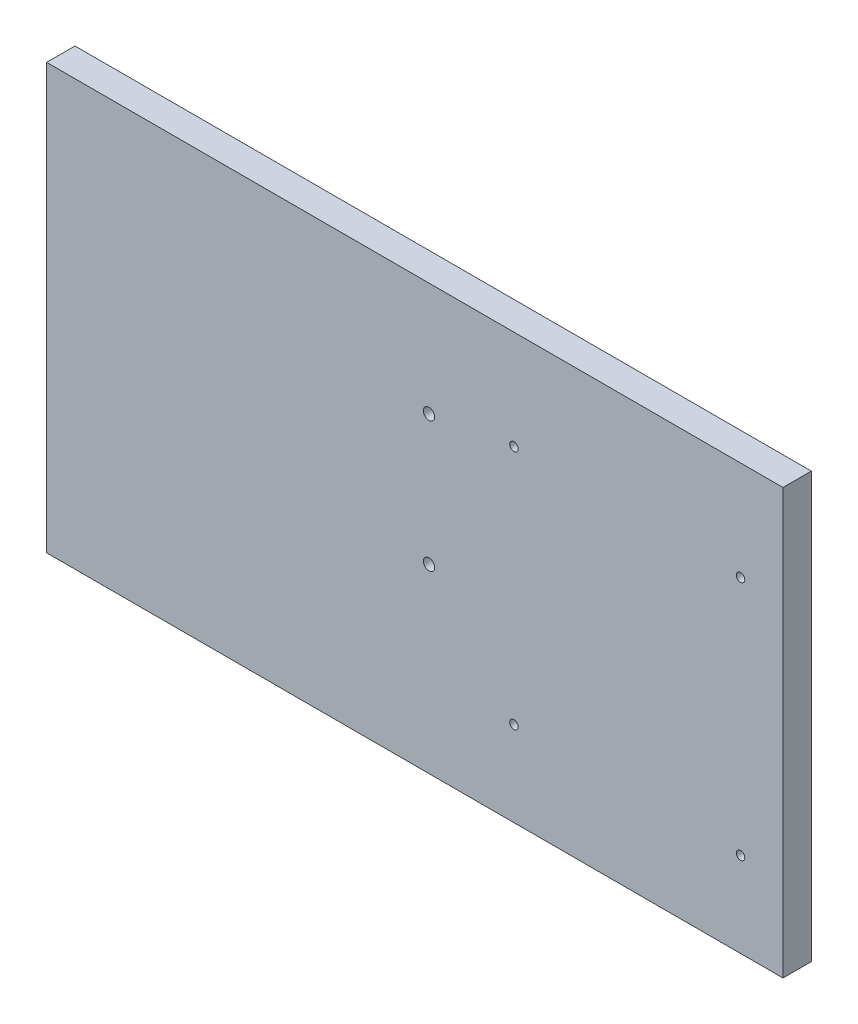
SolidWorks part; units mm, degrees
material "Faia"
ref_plane "Plano frontal" through (0, 0, 0) normal (0, 0, 1) x (1, 0, 0)
ref_plane "Plano superior" through (0, 0, 0) normal (0, 1, 0) x (1, 0, 0)
ref_plane "Plano direito" through (0, 0, 0) normal (1, 0, 0) x (0, 0, -1)
sketch "Esboço1" plane through (0, 0, 0) normal (0, 0, 1) x (1, 0, 0)
  line L0 (130, 0) -> (-130, 0) construction
  line L1 (-130, 75) -> (130, 75)
  line L2 (-130, 75) -> (-130, -75)
  line L3 (-130, -75) -> (130, -75)
  line L4 (130, 75) -> (130, -75)
  line L5 (-130, 75) -> (130, -75) construction
  line L6 (-130, -75) -> (130, 75) construction
  line L7 (50, 0) -> (-210, 0) construction
  line L8 (5, -11) -> (5, 35) construction
  line L9 (35, 40) -> (35, -45) construction
  line L10 (115, 40) -> (35, 40) construction
  circle A0 centre (115, 40) radius 1.5
  circle A1 centre (115, -45) radius 1.5
  circle A2 centre (35, -45) radius 1.5
  circle A3 centre (35, 40) radius 1.5
  circle A4 centre (5, 35) radius 2
  circle A5 centre (5, -11) radius 2
  point P0 (0, 0)
  point P21 (5, 0)
  point P23 (0, 0)
  point P24 (0, 0)
  dimension "D5" = 3
  dimension "D8" = 4
  dimension "D1" = 260
  dimension "D2" = 150
  dimension "D3" = 15
  dimension "D4" = 85
  dimension "D7" = 80
  dimension "D9" = 46
  dimension "D10" = 125
  dimension "D11" = 40
  dimension "D12" = 5
  dimension "D6" = 2
extrude "Ressalto-extrusão1" add sketch "Esboço1" along normal blind 10 contours L4 L1 L2 L3 A3 A1 A0 A2
